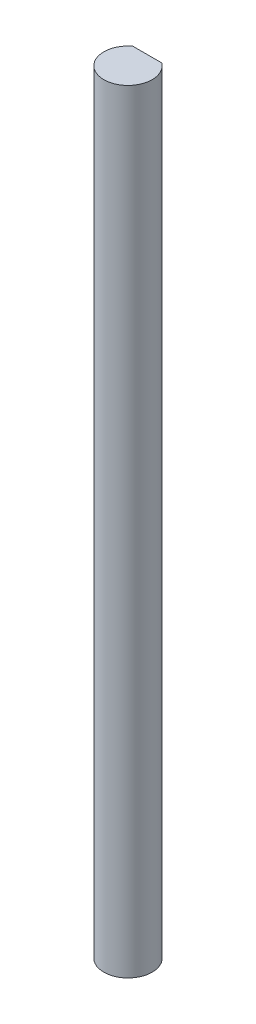
SolidWorks part; units mm, degrees
material "AISI 304"
ref_plane "Front Plane" through (0, 0, 0) normal (0, 0, 1) x (1, 0, 0)
ref_plane "Top Plane" through (0, 0, 0) normal (0, 1, 0) x (1, 0, 0)
ref_plane "Right Plane" through (0, 0, 0) normal (1, 0, 0) x (0, 0, -1)
sketch "Sketch1" plane through (0, 0, 0) normal (0, 1, 0) x (1, 0, 0)
  line L0 (-1.905, 2.54) -> (1.905, 2.54)
  arc A0 (-1.905, 2.54) -> (1.905, 2.54) centre (0, 0) ccw
  point P4 (2.2622, 2.2278)
  dimension "D1" = 6.35
  dimension "D2" = 2.54
extrude "Boss-Extrude1" add sketch "Sketch1" along normal blind 101.6
